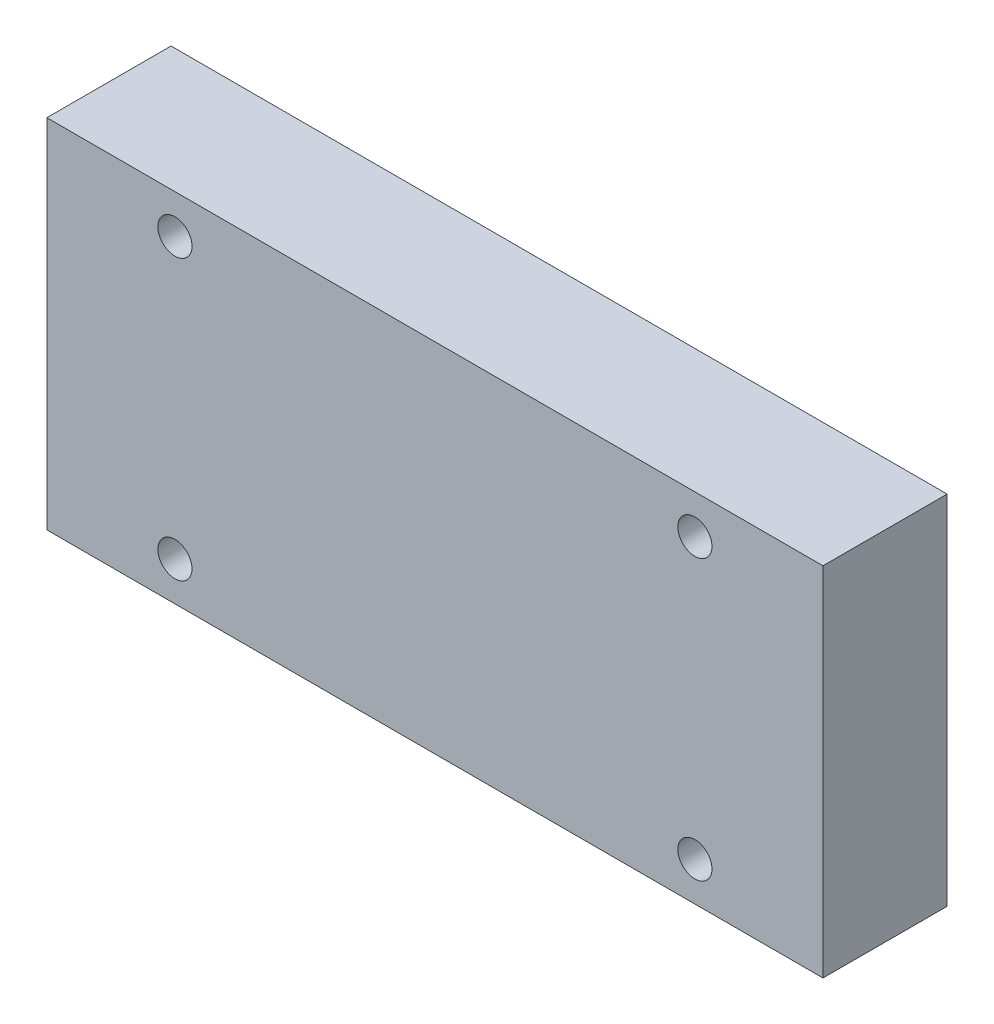
SolidWorks part; units mm, degrees
ref_plane "Ebene vorne" through (0, 0, 0) normal (0, 0, 1) x (1, 0, 0)
ref_plane "Ebene oben" through (0, 0, 0) normal (0, 1, 0) x (1, 0, 0)
ref_plane "Ebene rechts" through (0, 0, 0) normal (1, 0, 0) x (0, 0, -1)
sketch "Sketch1" plane through (0, 0, 0) normal (0, 0, 1) x (1, 0, 0)
  line L0 (0, 34.0626) -> (0, -27.7624) construction
  line L1 (-25, 11.5) -> (25, 11.5)
  line L2 (-25, 11.5) -> (-25, -11.5)
  line L3 (-25, -11.5) -> (25, -11.5)
  line L4 (25, 11.5) -> (25, -11.5)
  line L6 (71.1577, 0) -> (-30.6563, 0) construction
  circle A0 centre (-16.75, 9) radius 1.1
  circle A1 centre (16.75, 9) radius 1.1
  circle A2 centre (-16.75, -9) radius 1.1
  circle A3 centre (16.75, -9) radius 1.1
  dimension "D3" = 2.2
  dimension "D1" = 50
  dimension "D2" = 23
  dimension "D4" = 33.5
  dimension "D5" = 18
extrude "Boss-Extrude1" add sketch "Sketch1" along normal blind 8
